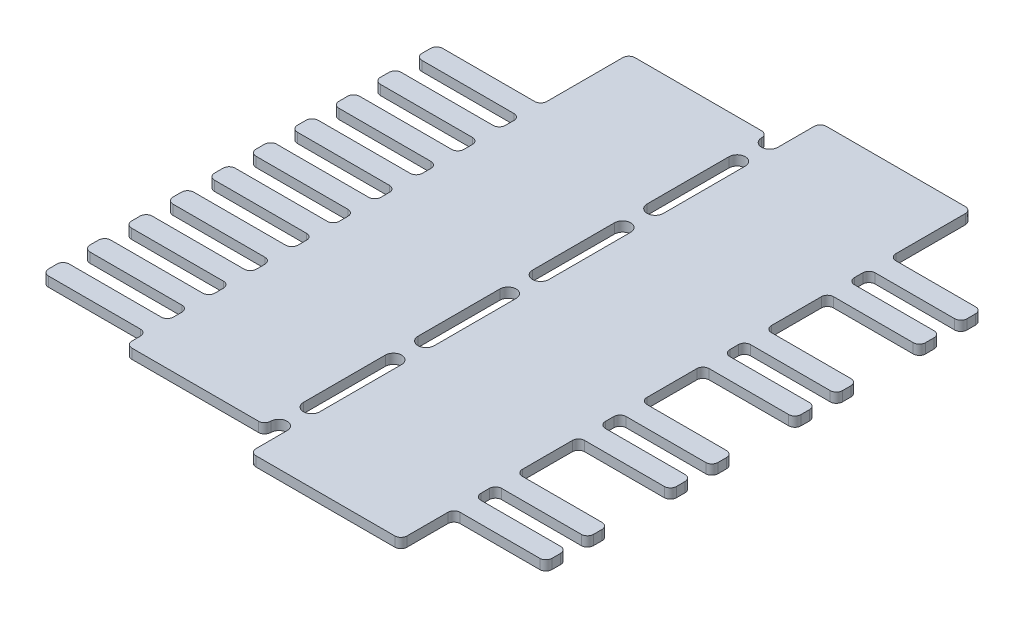
SolidWorks part; units mm, degrees
ref_plane "Front Plane" through (0, 0, 0) normal (0, 0, 1) x (1, 0, 0)
ref_plane "Top Plane" through (0, 0, 0) normal (0, 1, 0) x (1, 0, 0)
ref_plane "Right Plane" through (0, 0, 0) normal (1, 0, 0) x (0, 0, -1)
sketch "Sketch1" plane through (0, 0, 0) normal (0, 1, 0) x (1, 0, 0)
  line L0 (-0.75, 10) -> (-10.5, 10)
  line L2 (0, 9.25) -> (0, 0.75)
  line L5 (-11.25, 11.27) -> (0, 11.27) construction
  line L7 (-11.25, 10.75) -> (-11.25, 11.79)
  line L8 (-10.5, 12.54) -> (-0.75, 12.54)
  line L12 (0, 14.33) -> (0, 13.29)
  line L17 (-0.75, 15.08) -> (-10.5, 15.08)
  line L22 (-11.25, 15.83) -> (-11.25, 16.87)
  line L27 (-10.5, 17.62) -> (-0.75, 17.62)
  line L56 (17.75, 0) -> (0.75, 0)
  line L84 (0, 19.41) -> (0, 10.91) [skipped]
  line L85 (-0.75, 20.16) -> (-10.5, 20.16) [skipped]
  line L86 (-11.25, 20.91) -> (-11.25, 21.95) [skipped]
  line L87 (-10.5, 22.7) -> (-0.75, 22.7) [skipped]
  line L88 (0, 24.49) -> (0, 15.99) [skipped]
  line L89 (-0.75, 25.24) -> (-10.5, 25.24) [skipped]
  line L90 (-11.25, 25.99) -> (-11.25, 27.03) [skipped]
  line L91 (-10.5, 27.78) -> (-0.75, 27.78) [skipped]
  line L92 (0, 29.57) -> (0, 21.07) [skipped]
  line L93 (-0.75, 30.32) -> (-10.5, 30.32) [skipped]
  line L94 (-11.25, 31.07) -> (-11.25, 32.11) [skipped]
  line L95 (-10.5, 32.86) -> (-0.75, 32.86) [skipped]
  line L96 (0, 34.65) -> (0, 26.15) [skipped]
  line L97 (-0.75, 35.4) -> (-10.5, 35.4) [skipped]
  line L98 (-11.25, 36.15) -> (-11.25, 37.19) [skipped]
  line L99 (-10.5, 37.94) -> (-0.75, 37.94) [skipped]
  line L100 (0, 39.73) -> (0, 31.23) [skipped]
  line L101 (-0.75, 40.48) -> (-10.5, 40.48) [skipped]
  line L102 (-11.25, 41.23) -> (-11.25, 42.27) [skipped]
  line L103 (-10.5, 43.02) -> (-0.75, 43.02) [skipped]
  line L104 (0, 44.81) -> (0, 36.31) [skipped]
  line L105 (-0.75, 45.56) -> (-10.5, 45.56) [skipped]
  line L106 (-11.25, 46.31) -> (-11.25, 47.35) [skipped]
  line L107 (-10.5, 48.1) -> (-0.75, 48.1) [skipped]
  line L108 (0, 49.89) -> (0, 41.39) [skipped]
  line L109 (-0.75, 50.64) -> (-10.5, 50.64) [skipped]
  line L110 (-11.25, 51.39) -> (-11.25, 52.43) [skipped]
  line L111 (-10.5, 53.18) -> (-0.75, 53.18) [skipped]
  line L112 (0, 54.97) -> (0, 46.47) [skipped]
  line L113 (-0.75, 55.72) -> (-10.5, 55.72) [skipped]
  line L114 (-11.25, 56.47) -> (-11.25, 57.51) [skipped]
  line L115 (-10.5, 58.26) -> (-0.75, 58.26) [skipped]
  line L116 (-0.75, 25.24) -> (-10.5, 25.24)
  line L117 (-11.25, 25.99) -> (-11.25, 27.03)
  line L118 (-10.5, 27.78) -> (-0.75, 27.78)
  line L119 (0, 29.57) -> (0, 28.53)
  line L120 (-0.75, 30.32) -> (-10.5, 30.32)
  line L121 (-11.25, 31.07) -> (-11.25, 32.11)
  line L122 (-10.5, 32.86) -> (-0.75, 32.86)
  line L123 (-0.75, 40.48) -> (-10.5, 40.48)
  line L124 (-11.25, 41.23) -> (-11.25, 42.27)
  line L125 (-10.5, 43.02) -> (-0.75, 43.02)
  line L126 (0, 44.81) -> (0, 43.77)
  line L127 (-0.75, 45.56) -> (-10.5, 45.56)
  line L128 (-11.25, 46.31) -> (-11.25, 47.35)
  line L129 (-10.5, 48.1) -> (-0.75, 48.1)
  line L130 (-0.75, 55.72) -> (-10.5, 55.72)
  line L131 (-11.25, 56.47) -> (-11.25, 57.51)
  line L132 (-10.5, 58.26) -> (-0.75, 58.26)
  line L133 (0, 60.05) -> (0, 59.01)
  line L134 (-0.75, 60.8) -> (-10.5, 60.8)
  line L135 (-11.25, 61.55) -> (-11.25, 62.59)
  line L136 (-10.5, 63.34) -> (-0.75, 63.34)
  line L137 (0, 24.49) -> (0, 18.37)
  line L138 (0, 33.61) -> (0, 39.73)
  line L139 (0, 48.85) -> (0, 54.97)
  line L140 (0, 64.09) -> (0, 69.09)
  line L141 (0.75, 69.84) -> (17.75, 69.84)
  line L145 (38.25, 15.2205) -> (49.5, 15.2205)
  line L157 (37.5, 14.4705) -> (37.5, 5.183)
  line L158 (36.75, 4.433) -> (21.25, 4.433)
  line L160 (21.25, 66.0205) -> (36.75, 66.0205)
  line L188 (19.5, 5.183) -> (19.5, 56.2098) construction
  line L190 (18.5, 0.75) -> (18.5, 5.183)
  line L191 (20.5, 5.183) -> (19.5, 5.183) construction
  line L192 (20.5, 65.2705) -> (19.5, 65.2705) construction
  line L193 (20, 56.7098) -> (20, 60.84) construction
  line L194 (19, 60.84) -> (19, 56.7098) construction
  line L195 (18.5, 65.2705) -> (18.5, 69.09)
  line L196 (19.5, 56.2098) -> (19.5, 57.2098) construction
  line L197 (19.5, 57.2098) -> (19.5, 60.34) construction
  line L198 (19.5, 60.34) -> (19.5, 61.34) construction
  line L199 (19.5, 61.34) -> (19.5, 65.2705) construction
  line L200 (50.25, 15.9705) -> (50.25, 17.0105)
  line L201 (49.5, 17.7605) -> (38.25, 17.7605)
  line L202 (37.5, 18.5105) -> (37.5, 19.5505)
  line L204 (50.25, 21.0505) -> (50.25, 22.0905)
  line L205 (49.5, 22.8405) -> (38.25, 22.8405)
  line L206 (37.5, 23.5905) -> (37.5, 24.6305)
  line L207 (38.25, 20.3005) -> (49.5, 20.3005)
  line L208 (50.25, 26.1305) -> (50.25, 27.1705)
  line L209 (49.5, 27.9205) -> (38.25, 27.9205)
  line L210 (37.5, 28.6705) -> (37.5, 29.7105)
  line L212 (19.5, 65.2705) -> (18.5, 65.2705) construction
  line L213 (19.5, 65.2705) -> (19.5, 59.9038) construction
  line L214 (38.25, 25.3805) -> (49.5, 25.3805)
  line L215 (50.25, 31.2105) -> (50.25, 32.2505)
  line L216 (49.5, 33.0005) -> (38.25, 33.0005)
  line L217 (37.5, 33.7505) -> (37.5, 34.7905)
  line L218 (19.5, 5.183) -> (18.5, 5.183) construction
  line L219 (38.25, 30.4605) -> (49.5, 30.4605)
  line L220 (50.25, 36.2905) -> (50.25, 37.3305)
  line L221 (49.5, 38.0805) -> (38.25, 38.0805)
  line L222 (37.5, 38.8305) -> (37.5, 39.8705)
  line L223 (38.25, 35.5405) -> (49.5, 35.5405)
  line L224 (50.25, 41.3705) -> (50.25, 42.4105)
  line L225 (49.5, 43.1605) -> (38.25, 43.1605)
  line L226 (37.5, 43.9105) -> (37.5, 44.9505)
  line L227 (38.25, 40.6205) -> (49.5, 40.6205)
  line L228 (50.25, 46.4505) -> (50.25, 47.4905)
  line L229 (49.5, 48.2405) -> (38.25, 48.2405)
  line L230 (37.5, 48.9905) -> (37.5, 50.0305)
  line L231 (38.25, 45.7005) -> (49.5, 45.7005)
  line L232 (50.25, 51.5305) -> (50.25, 52.5705)
  line L233 (49.5, 53.3205) -> (38.25, 53.3205)
  line L234 (37.5, 54.0705) -> (37.5, 55.1105)
  line L235 (38.25, 50.7805) -> (49.5, 50.7805)
  line L236 (50.25, 56.6105) -> (50.25, 57.6505)
  line L237 (49.5, 58.4005) -> (38.25, 58.4005)
  line L238 (37.5, 59.1505) -> (37.5, 60.1905)
  line L239 (38.25, 55.8605) -> (49.5, 55.8605)
  line L240 (50.25, 61.6905) -> (50.25, 62.7305)
  line L241 (49.5, 63.4805) -> (38.25, 63.4805)
  line L242 (37.5, 64.2305) -> (37.5, 65.2705)
  line L243 (38.25, 60.9405) -> (49.5, 60.9405)
  arc A0 (-0.75, 12.54) -> (0, 13.29) centre (-0.75, 13.29) ccw
  arc A1 (-11.25, 11.79) -> (-10.5, 12.54) centre (-10.5, 11.79) cw
  arc A2 (-10.5, 10) -> (-11.25, 10.75) centre (-10.5, 10.75) cw
  arc A3 (0, 0.75) -> (0.75, 0) centre (0.75, 0.75) ccw
  arc A4 (-0.75, 10) -> (0, 9.25) centre (-0.75, 9.25) cw
  arc A5 (18.5, 0.75) -> (17.75, 0) centre (17.75, 0.75) cw
  arc A6 (-0.75, 15.08) -> (0, 14.33) centre (-0.75, 14.33) cw
  arc A7 (-10.5, 15.08) -> (-11.25, 15.83) centre (-10.5, 15.83) cw
  arc A8 (-11.25, 16.87) -> (-10.5, 17.62) centre (-10.5, 16.87) cw
  arc A9 (-0.75, 17.62) -> (0, 18.37) centre (-0.75, 18.37) ccw
  arc A44 (-0.75, 20.16) -> (0, 19.41) centre (-0.75, 19.41) cw [skipped]
  arc A45 (-10.5, 20.16) -> (-11.25, 20.91) centre (-10.5, 20.91) cw [skipped]
  arc A46 (-11.25, 21.95) -> (-10.5, 22.7) centre (-10.5, 21.95) cw [skipped]
  arc A47 (-0.75, 22.7) -> (0, 23.45) centre (-0.75, 23.45) ccw [skipped]
  arc A48 (-0.75, 25.24) -> (0, 24.49) centre (-0.75, 24.49) cw [skipped]
  arc A49 (-10.5, 25.24) -> (-11.25, 25.99) centre (-10.5, 25.99) cw [skipped]
  arc A50 (-11.25, 27.03) -> (-10.5, 27.78) centre (-10.5, 27.03) cw [skipped]
  arc A51 (-0.75, 27.78) -> (0, 28.53) centre (-0.75, 28.53) ccw [skipped]
  arc A52 (-0.75, 30.32) -> (0, 29.57) centre (-0.75, 29.57) cw [skipped]
  arc A53 (-10.5, 30.32) -> (-11.25, 31.07) centre (-10.5, 31.07) cw [skipped]
  arc A54 (-11.25, 32.11) -> (-10.5, 32.86) centre (-10.5, 32.11) cw [skipped]
  arc A55 (-0.75, 32.86) -> (0, 33.61) centre (-0.75, 33.61) ccw [skipped]
  arc A56 (-0.75, 35.4) -> (0, 34.65) centre (-0.75, 34.65) cw [skipped]
  arc A57 (-10.5, 35.4) -> (-11.25, 36.15) centre (-10.5, 36.15) cw [skipped]
  arc A58 (-11.25, 37.19) -> (-10.5, 37.94) centre (-10.5, 37.19) cw [skipped]
  arc A59 (-0.75, 37.94) -> (0, 38.69) centre (-0.75, 38.69) ccw [skipped]
  arc A60 (-0.75, 40.48) -> (0, 39.73) centre (-0.75, 39.73) cw [skipped]
  arc A61 (-10.5, 40.48) -> (-11.25, 41.23) centre (-10.5, 41.23) cw [skipped]
  arc A62 (-11.25, 42.27) -> (-10.5, 43.02) centre (-10.5, 42.27) cw [skipped]
  arc A63 (-0.75, 43.02) -> (0, 43.77) centre (-0.75, 43.77) ccw [skipped]
  arc A64 (-0.75, 45.56) -> (0, 44.81) centre (-0.75, 44.81) cw [skipped]
  arc A65 (-10.5, 45.56) -> (-11.25, 46.31) centre (-10.5, 46.31) cw [skipped]
  arc A66 (-11.25, 47.35) -> (-10.5, 48.1) centre (-10.5, 47.35) cw [skipped]
  arc A67 (-0.75, 48.1) -> (0, 48.85) centre (-0.75, 48.85) ccw [skipped]
  arc A68 (-0.75, 50.64) -> (0, 49.89) centre (-0.75, 49.89) cw [skipped]
  arc A69 (-10.5, 50.64) -> (-11.25, 51.39) centre (-10.5, 51.39) cw [skipped]
  arc A70 (-11.25, 52.43) -> (-10.5, 53.18) centre (-10.5, 52.43) cw [skipped]
  arc A71 (-0.75, 53.18) -> (0, 53.93) centre (-0.75, 53.93) ccw [skipped]
  arc A72 (-0.75, 55.72) -> (0, 54.97) centre (-0.75, 54.97) cw [skipped]
  arc A73 (-10.5, 55.72) -> (-11.25, 56.47) centre (-10.5, 56.47) cw [skipped]
  arc A74 (-11.25, 57.51) -> (-10.5, 58.26) centre (-10.5, 57.51) cw [skipped]
  arc A75 (-0.75, 58.26) -> (0, 59.01) centre (-0.75, 59.01) ccw [skipped]
  arc A76 (-0.75, 27.78) -> (0, 28.53) centre (-0.75, 28.53) ccw
  arc A77 (-11.25, 27.03) -> (-10.5, 27.78) centre (-10.5, 27.03) cw
  arc A78 (-10.5, 25.24) -> (-11.25, 25.99) centre (-10.5, 25.99) cw
  arc A79 (-0.75, 25.24) -> (0, 24.49) centre (-0.75, 24.49) cw
  arc A80 (-0.75, 30.32) -> (0, 29.57) centre (-0.75, 29.57) cw
  arc A81 (-10.5, 30.32) -> (-11.25, 31.07) centre (-10.5, 31.07) cw
  arc A82 (-11.25, 32.11) -> (-10.5, 32.86) centre (-10.5, 32.11) cw
  arc A83 (-0.75, 32.86) -> (0, 33.61) centre (-0.75, 33.61) ccw
  arc A84 (-0.75, 43.02) -> (0, 43.77) centre (-0.75, 43.77) ccw
  arc A85 (-11.25, 42.27) -> (-10.5, 43.02) centre (-10.5, 42.27) cw
  arc A86 (-10.5, 40.48) -> (-11.25, 41.23) centre (-10.5, 41.23) cw
  arc A87 (-0.75, 40.48) -> (0, 39.73) centre (-0.75, 39.73) cw
  arc A88 (-0.75, 45.56) -> (0, 44.81) centre (-0.75, 44.81) cw
  arc A89 (-10.5, 45.56) -> (-11.25, 46.31) centre (-10.5, 46.31) cw
  arc A90 (-11.25, 47.35) -> (-10.5, 48.1) centre (-10.5, 47.35) cw
  arc A91 (-0.75, 48.1) -> (0, 48.85) centre (-0.75, 48.85) ccw
  arc A92 (-0.75, 58.26) -> (0, 59.01) centre (-0.75, 59.01) ccw
  arc A93 (-11.25, 57.51) -> (-10.5, 58.26) centre (-10.5, 57.51) cw
  arc A94 (-10.5, 55.72) -> (-11.25, 56.47) centre (-10.5, 56.47) cw
  arc A95 (-0.75, 55.72) -> (0, 54.97) centre (-0.75, 54.97) cw
  arc A96 (-0.75, 60.8) -> (0, 60.05) centre (-0.75, 60.05) cw
  arc A97 (-10.5, 60.8) -> (-11.25, 61.55) centre (-10.5, 61.55) cw
  arc A98 (-11.25, 62.59) -> (-10.5, 63.34) centre (-10.5, 62.59) cw
  arc A99 (-0.75, 63.34) -> (0, 64.09) centre (-0.75, 64.09) ccw
  arc A100 (0, 69.09) -> (0.75, 69.84) centre (0.75, 69.09) cw
  arc A101 (17.75, 69.84) -> (18.5, 69.09) centre (17.75, 69.09) cw
  arc A107 (20.5, 65.2705) -> (21.25, 66.0205) centre (21.25, 65.2705) cw
  arc A144 (37.5, 5.183) -> (36.75, 4.433) centre (36.75, 5.183) cw
  arc A145 (21.25, 4.433) -> (20.5, 5.183) centre (21.25, 5.183) cw
  arc A147 (20.5, 5.183) -> (18.5, 5.183) centre (19.5, 5.183) ccw
  arc A148 (18.5, 5.183) -> (20.5, 5.183) centre (19.5, 5.183) ccw construction
  arc A149 (20, 60.84) -> (19, 60.84) centre (19.5, 60.84) ccw construction
  arc A150 (19, 56.7098) -> (20, 56.7098) centre (19.5, 56.7098) ccw construction
  arc A151 (19.5, 57.2098) -> (19, 56.7098) centre (19.5, 56.7098) ccw construction
  arc A152 (20, 56.7098) -> (19.5, 57.2098) centre (19.5, 56.7098) ccw construction
  arc A153 (19.5, 60.34) -> (20, 60.84) centre (19.5, 60.84) ccw construction
  arc A154 (19, 60.84) -> (19.5, 60.34) centre (19.5, 60.84) ccw construction
  arc A155 (18.5, 65.2705) -> (20.5, 65.2705) centre (19.5, 65.2705) ccw
  arc A156 (20.5, 65.2705) -> (18.5, 65.2705) centre (19.5, 65.2705) ccw construction
  arc A157 (38.25, 17.7605) -> (37.5, 18.5105) centre (38.25, 18.5105) cw
  arc A158 (50.25, 17.0105) -> (49.5, 17.7605) centre (49.5, 17.0105) ccw
  arc A159 (49.5, 15.2205) -> (50.25, 15.9705) centre (49.5, 15.9705) ccw
  arc A160 (37.5, 14.4705) -> (38.25, 15.2205) centre (38.25, 14.4705) cw
  arc A161 (38.25, 22.8405) -> (37.5, 23.5905) centre (38.25, 23.5905) cw
  arc A162 (50.25, 22.0905) -> (49.5, 22.8405) centre (49.5, 22.0905) ccw
  arc A163 (49.5, 20.3005) -> (50.25, 21.0505) centre (49.5, 21.0505) ccw
  arc A164 (37.5, 19.5505) -> (38.25, 20.3005) centre (38.25, 19.5505) cw
  arc A165 (38.25, 27.9205) -> (37.5, 28.6705) centre (38.25, 28.6705) cw
  arc A166 (50.25, 27.1705) -> (49.5, 27.9205) centre (49.5, 27.1705) ccw
  arc A167 (49.5, 25.3805) -> (50.25, 26.1305) centre (49.5, 26.1305) ccw
  arc A168 (37.5, 24.6305) -> (38.25, 25.3805) centre (38.25, 24.6305) cw
  arc A169 (38.25, 33.0005) -> (37.5, 33.7505) centre (38.25, 33.7505) cw
  arc A170 (50.25, 32.2505) -> (49.5, 33.0005) centre (49.5, 32.2505) ccw
  arc A171 (49.5, 30.4605) -> (50.25, 31.2105) centre (49.5, 31.2105) ccw
  arc A172 (37.5, 29.7105) -> (38.25, 30.4605) centre (38.25, 29.7105) cw
  arc A173 (38.25, 38.0805) -> (37.5, 38.8305) centre (38.25, 38.8305) cw
  arc A174 (50.25, 37.3305) -> (49.5, 38.0805) centre (49.5, 37.3305) ccw
  arc A175 (49.5, 35.5405) -> (50.25, 36.2905) centre (49.5, 36.2905) ccw
  arc A176 (37.5, 34.7905) -> (38.25, 35.5405) centre (38.25, 34.7905) cw
  arc A177 (38.25, 43.1605) -> (37.5, 43.9105) centre (38.25, 43.9105) cw
  arc A178 (50.25, 42.4105) -> (49.5, 43.1605) centre (49.5, 42.4105) ccw
  arc A179 (49.5, 40.6205) -> (50.25, 41.3705) centre (49.5, 41.3705) ccw
  arc A180 (37.5, 39.8705) -> (38.25, 40.6205) centre (38.25, 39.8705) cw
  arc A181 (38.25, 48.2405) -> (37.5, 48.9905) centre (38.25, 48.9905) cw
  arc A182 (50.25, 47.4905) -> (49.5, 48.2405) centre (49.5, 47.4905) ccw
  arc A183 (49.5, 45.7005) -> (50.25, 46.4505) centre (49.5, 46.4505) ccw
  arc A184 (37.5, 44.9505) -> (38.25, 45.7005) centre (38.25, 44.9505) cw
  arc A185 (38.25, 53.3205) -> (37.5, 54.0705) centre (38.25, 54.0705) cw
  arc A186 (50.25, 52.5705) -> (49.5, 53.3205) centre (49.5, 52.5705) ccw
  arc A187 (49.5, 50.7805) -> (50.25, 51.5305) centre (49.5, 51.5305) ccw
  arc A188 (37.5, 50.0305) -> (38.25, 50.7805) centre (38.25, 50.0305) cw
  arc A189 (38.25, 58.4005) -> (37.5, 59.1505) centre (38.25, 59.1505) cw
  arc A190 (50.25, 57.6505) -> (49.5, 58.4005) centre (49.5, 57.6505) ccw
  arc A191 (49.5, 55.8605) -> (50.25, 56.6105) centre (49.5, 56.6105) ccw
  arc A192 (37.5, 55.1105) -> (38.25, 55.8605) centre (38.25, 55.1105) cw
  arc A193 (38.25, 63.4805) -> (37.5, 64.2305) centre (38.25, 64.2305) cw
  arc A194 (50.25, 62.7305) -> (49.5, 63.4805) centre (49.5, 62.7305) ccw
  arc A195 (49.5, 60.9405) -> (50.25, 61.6905) centre (49.5, 61.6905) ccw
  arc A196 (37.5, 60.1905) -> (38.25, 60.9405) centre (38.25, 60.1905) cw
  arc A197 (37.5, 65.2705) -> (36.75, 66.0205) centre (36.75, 65.2705) ccw
  point P0 (0, 0)
  point P48 (-11.25, 12.54)
  point P69 (-11.25, 10)
  point P78 (0, 0)
  point P81 (0, 10)
  point P132 (29, 4.433)
  point P390 (43.875, 15.2205)
  dimension "D6" = 0.75
  dimension "D7" = 0.75
  dimension "D8" = 4
  dimension "D9" = 10.16
  dimension "D11" = 0.75
  dimension "D13" = 4.433
  dimension "D14" = 0.75
  dimension "D15" = 9
  dimension "D16" = 0.75
  dimension "D12" = 6.5
  dimension "D21" = 0.75
  dimension "D22" = 18.5
  dimension "D5" = 2
  dimension "D24" = 4.1302
  dimension "D25" = 17
  dimension "D17" = 0.75
  dimension "D1" = 2.54
  dimension "D2" = 10.5
  dimension "D3" = 10
  dimension "D4" = 10
  dimension "D10" = 5.08
  dimension "D18" = 10
  dimension "D19" = 12
  dimension "D20" = 2.54
  dimension "D23" = 5.08
  dimension "D26" = 10.7875
  dimension "D27" = 69.84
  dimension "D28" = 3.8195
  dimension "D29" = 3.8195
extrude "Boss-Extrude1" add sketch "Sketch1" along normal blind 1.2
sketch "Sketch2" plane through (0, 0, 0) normal (0, -1, 0) x (1, 0, 0)
  line L0 (19.5, -5.183) -> (19.5, -65.2705) construction
  line L1 (19.5, -61.2705) -> (19.5, -51.2505) construction
  line L2 (18.5, -61.2705) -> (18.5, -51.2505)
  line L3 (20.5, -61.2705) -> (20.5, -51.2505)
  line L4 (19.5, -35.2268) -> (0, -35.2268) construction
  line L5 (0, -39.73) -> (0, -33.61) construction
  line L6 (19.5, -47.2505) -> (19.5, -37.2305) construction
  line L7 (18.5, -47.2505) -> (18.5, -37.2305)
  line L8 (20.5, -47.2505) -> (20.5, -37.2305)
  line L9 (19.5, -23.203) -> (19.5, -33.223) construction
  line L10 (18.5, -23.203) -> (18.5, -33.223)
  line L11 (20.5, -23.203) -> (20.5, -33.223)
  line L12 (19.5, -9.183) -> (19.5, -19.203) construction
  line L13 (18.5, -9.183) -> (18.5, -19.203)
  line L14 (20.5, -9.183) -> (20.5, -19.203)
  arc A0 (18.5, -61.2705) -> (20.5, -61.2705) centre (19.5, -61.2705) ccw
  arc A1 (20.5, -51.2505) -> (18.5, -51.2505) centre (19.5, -51.2505) ccw
  circle A2 centre (19.5, -65.2705) radius 1 construction
  arc A3 (20.5, -65.2705) -> (18.5, -65.2705) centre (19.5, -65.2705) ccw construction
  arc A4 (18.5, -47.2505) -> (20.5, -47.2505) centre (19.5, -47.2505) ccw
  arc A5 (20.5, -37.2305) -> (18.5, -37.2305) centre (19.5, -37.2305) ccw
  arc A6 (18.5, -23.203) -> (20.5, -23.203) centre (19.5, -23.203) cw
  arc A7 (20.5, -33.223) -> (18.5, -33.223) centre (19.5, -33.223) cw
  arc A8 (18.5, -9.183) -> (20.5, -9.183) centre (19.5, -9.183) cw
  arc A9 (20.5, -19.203) -> (18.5, -19.203) centre (19.5, -19.203) cw
  point P6 (19.5, -56.2605)
  point P23 (19.5, -42.2405)
  point P28 (19.5, -28.213)
  point P35 (19.5, -14.193)
  dimension "D4" = 4
  dimension "D1" = 10.02
  dimension "D2" = 4
  dimension "D3" = 2
extrude "Cut-Extrude1" cut sketch "Sketch2" against normal through all
move or copy body "Body-Move/Copy1" bodies to move or copy 102 copy no rotation origin (17.625, 0, -34.92) rotation axis (0, 1, 0) rotation angle 180
equation "\"T\"= 1"
